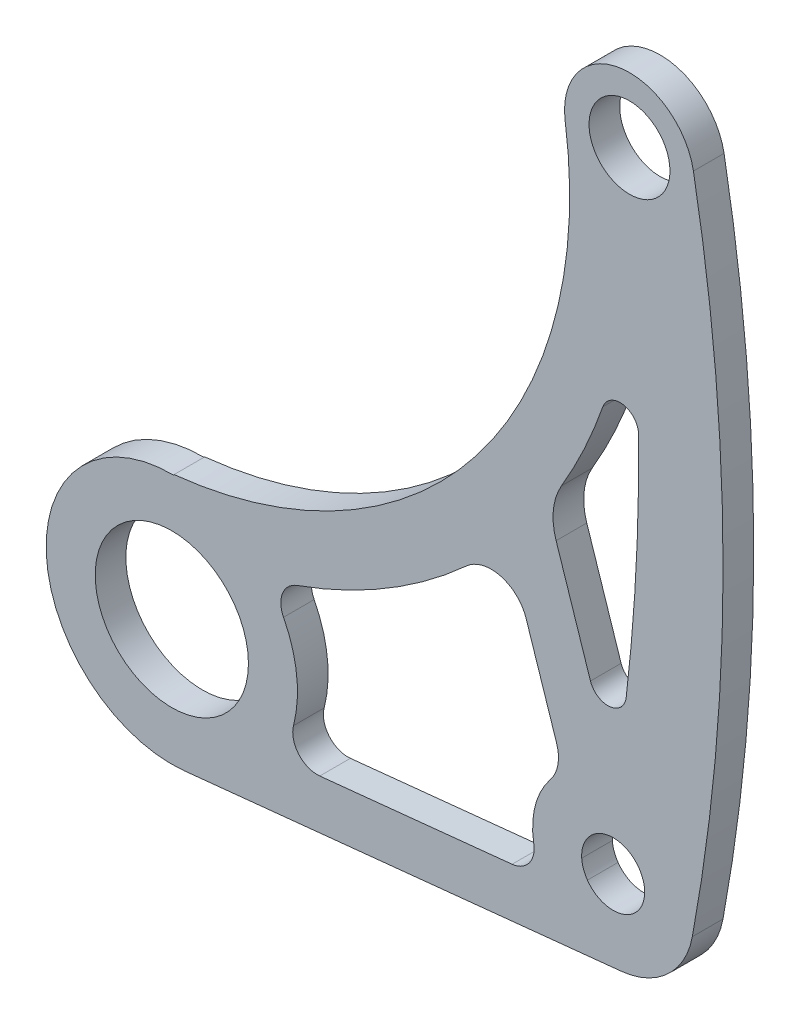
SolidWorks part; units mm, degrees
material "6061-T6 (SS)"
ref_plane "Front Plane" through (0, 0, 0) normal (0, 0, 1) x (1, 0, 0)
ref_plane "Top Plane" through (0, 0, 0) normal (0, 1, 0) x (1, 0, 0)
ref_plane "Right Plane" through (0, 0, 0) normal (1, 0, 0) x (0, 0, -1)
sketch "Sketch2" plane through (0, 0, 0) normal (0, 0, 1) x (1, 0, 0)
  line L0 (0, 0) -> (45.72, 0) construction
  line L1 (45.72, 0) -> (47.4133, 66.0183) construction
  line L2 (47.4133, 66.0183) -> (0, 0) construction
  line L3 (-9.9543, 8.3886) -> (42.2663, 70.3558)
  line L4 (54.1443, 66.0101) -> (54.0639, -0.0102)
  line L5 (46.5729, -8.3002) -> (1.3307, -12.9493)
  line L6 (-6.2268, 4.9225) -> (44.1256, 68.6173)
  line L7 (0.8114, -7.8959) -> (46.0536, -3.2468)
  line L8 (48.9813, -0.1295) -> (51.601, 65.852)
  line L10 (45.72, 0) -> (38.8832, 9.7026) construction
  line L11 (45.72, 0) -> (42.0108, 11.275) construction
  line L12 (45.72, 0) -> (44.9726, 11.8459) construction
  line L13 (47.2407, 59.2895) -> (45.9339, 8.3412)
  line L14 (45.72, 0) -> (36.8585, 26.9366) construction
  line L15 (34.7499, 24.3546) -> (40.5957, 6.585)
  line L16 (38.8824, 29.7758) -> (45.9339, 8.3412)
  line L17 (41.2892, 13.4683) -> (38.6201, 12.5902) construction
  line L18 (41.2892, 13.4683) -> (43.9584, 14.3464) construction
  circle A0 centre (0, 0) radius 7.9375
  circle A1 centre (45.72, 0) radius 3.2639
  circle A2 centre (47.4133, 66.0183) radius 4.191
  circle A3 centre (0, 0) radius 13.0175
  circle A4 centre (45.72, 0) radius 8.3439
  circle A5 centre (47.4133, 66.0183) radius 6.731
  circle A8 centre (-4.5053, 58.5645) radius 45.72
  circle A9 centre (-4.5053, 58.5645) radius 52.07
  circle A10 centre (-133.3933, 33.155) radius 190.5
  circle A11 centre (-142.1385, 38.656) radius 190.5
  point P29 (47.2407, 59.2895)
  point P30 (45.72, 0)
  dimension "D1" = 8.382
  dimension "D2" = 6.5278
  dimension "D3" = 15.875
  dimension "D13" = 381
  dimension "D14" = 381
  dimension "2.7" = 45.72
  dimension "D5" = 66.04
  dimension "D6" = 5.08
  dimension "D7" = 2.54
  dimension "D8" = 5.08
  dimension "D9" = 81.28
  dimension "D4" = 54.83
  dimension "D10" = 71.79
  dimension "D11" = 86.39
  dimension "D12" = 6.35
extrude "Boss-Extrude1" add sketch "Sketch2" along normal blind 3.175 contours A3 A9 L13 A5 L6 A8 | A4 A10 A5 L4 | A5 L8 A4 L4 | A11 A4 L8 A5 A9 | A11 A9 A5 | A9 A11 L13 | A9 A5 L8 A2 | A11 A5 A9 A2 | A9 A2 L8 A5 | A2 A11 A5 L6 | A11 A2 A9 A5 | A5 A11 A2 L6 | L6 A9 A0 A3 | A3 A9 L6 | A9 A3 L7 A0 L6 | A9 L6 A0 | A9 A0 L7 A3 | L5 A11 A4 L7 A3 | A11 L5 A4 | A11 A4 L8 A1 L7 | A4 A11 L7 | L7 A11 A1 A4 | A11 L7 A1 | A11 A1 L8 A4 | A8 L6 A5 | A9 L15 A4 L16
ref_plane "Plane2" through (45.72, 0, 0) normal (-0.576, 0.8174, 0) x (0.8174, 0.576, 0)
split line "Split Line2"
ref_plane "Plane3" through (45.72, 0, 0) normal (-0.063, 0.998, 0) x (0.998, 0.063, 0)
split line "Split Line3"
fillet "Fillet1" radius 2.54 3 edges at (11.0749, -6.8412, 1.5875) (38.4148, -4.0318, 1.5875) (9.8489, 8.5121, 1.5875)
fillet "Fillet2" radius 3.81 2 edges at (40.5957, 6.585, 1.5875) (34.7499, 24.3546, 1.5875)
fillet "Fillet3" radius 1.905 2 edges at (45.9339, 8.3412, 1.5875) (47.5238, 56.5014, 1.5875)
fillet "Fillet4" radius 6.35 1 edges at (38.8824, 29.7758, 1.5875)
equation "\"Droop angle\"= 54.83"
equation "\"Static angle\"= 71.79"
equation "\"Jounce angle\"= 86.39"
equation "\"D4@Sketch2\"=\"Droop angle\""
equation "\"D10@Sketch2\"=\"Static angle\""
equation "\"D11@Sketch2\"=\"Jounce angle\""
